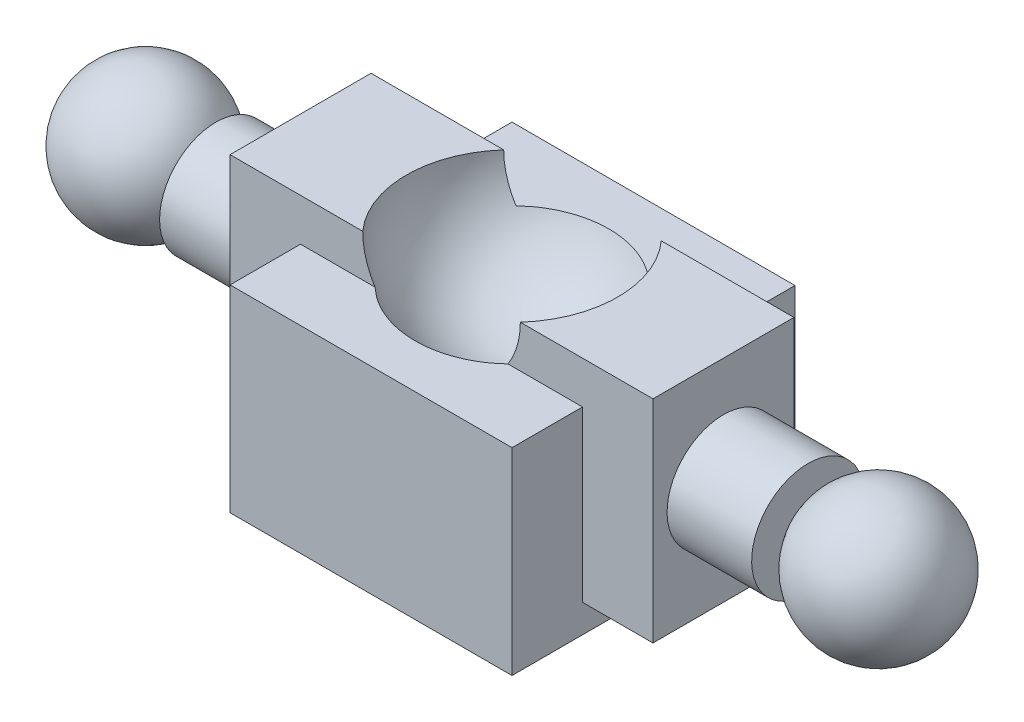
SolidWorks part; units mm, degrees
ref_plane "Front Plane" through (0, 0, 0) normal (0, 0, 1) x (1, 0, 0)
ref_plane "Top Plane" through (0, 0, 0) normal (0, 1, 0) x (1, 0, 0)
ref_plane "Right Plane" through (0, 0, 0) normal (1, 0, 0) x (0, 0, -1)
sketch "Sketch1" plane through (0, 0, 0) normal (0, 0, 1) x (1, 0, 0)
  line L1 (-11.2928, 4.8194) -> (18.7072, 4.8194)
  line L2 (-11.2928, 4.8194) -> (-11.2928, -10.1806)
  line L3 (-11.2928, -10.1806) -> (18.7072, -10.1806)
  line L4 (18.7072, 4.8194) -> (18.7072, -10.1806)
  dimension "D1" = 30
  dimension "D2" = 15
extrude "Boss-Extrude1" add sketch "Sketch1" along normal blind 10 contours L2 L1 L4 L3
sketch "Sketch2" plane through (0, 0, 10) normal (0, 0, 1) x (1, 0, 0)
  line L0 (-11.2928, 4.8194) -> (-11.2928, -10.1806) construction
  line L1 (-6.2928, 1.8194) -> (13.7072, 1.8194)
  line L2 (-6.2928, 1.8194) -> (-6.2928, -12.1806)
  line L3 (-6.2928, -12.1806) -> (13.7072, -12.1806)
  line L4 (13.7072, 1.8194) -> (13.7072, -12.1806)
  line L5 (18.7072, 4.8194) -> (18.7072, -10.1806) construction
  line L6 (-11.2928, 4.8194) -> (18.7072, 4.8194) construction
  line L7 (-11.2928, -10.1806) -> (18.7072, -10.1806) construction
  line L8 (-6.2928, -12.1806) -> (13.7072, -12.1806)
  line L9 (-6.2928, -12.1806) -> (-6.2928, -11.6554)
  line L11 (13.7072, -12.1806) -> (13.7072, -11.6554)
  dimension "D1" = 5
  dimension "D2" = 5
  dimension "D3" = 3
  dimension "D4" = 2
extrude "Boss-Extrude2" add sketch "Sketch2" along normal blind 5 contours L2 L1 L4 L3
sketch "Sketch3" plane through (0, 0, 0) normal (0, 0, -1) x (-1, 0, 0)
  line L0 (11.2928, 4.8194) -> (-18.7072, 4.8194) construction
  line L1 (6.2928, -12.1806) -> (-13.782, -12.1806)
  line L2 (6.2928, -12.1806) -> (6.2928, 1.8194)
  line L3 (6.2928, 1.8194) -> (-13.782, 1.8194)
  line L4 (-13.782, -12.1806) -> (-13.782, 1.8194)
  dimension "D1" = 3
extrude "Boss-Extrude3" add sketch "Sketch3" along normal blind 5 contours L2 L1 L4 L3
sketch "Sketch4" plane through (0, -10.1806, 0) normal (0, -1, 0) x (1, 0, 0)
  line L1 (-6.2928, 10) -> (13.7072, 10)
  line L2 (-6.2928, 10) -> (-6.2928, 0)
  line L3 (-6.2928, 0) -> (13.7072, 0)
  line L4 (13.7072, 10) -> (13.7072, 0)
extrude "Boss-Extrude4" add sketch "Sketch4" along normal blind 2
sketch "Sketch5" plane through (18.7072, 0, 0) normal (1, 0, 0) x (0, 0, -1)
  circle A0 centre (-5, -2.6514) radius 4
  dimension "D1" = 8
extrude "Boss-Extrude6" add sketch "Sketch5" along normal blind 6 contours A0
sketch "Sketch6" plane through (-11.2928, 0, 0) normal (-1, 0, 0) x (0, 0, 1)
  circle A0 centre (5, -2.6806) radius 4
  dimension "D1" = 8
extrude "Boss-Extrude7" add sketch "Sketch6" along normal blind 6
sketch "Sketch7" plane through (0, 4.8194, 0) normal (0, 1, 0) x (1, 0, 0)
  line L0 (3.7072, 2.5) -> (3.7072, -12.5)
  arc A0 (3.7072, 2.5) -> (3.7072, -12.5) centre (3.7072, -5) ccw
  dimension "D1" = 15
sketch "Sketch8" plane through (-17.2928, 0, 0) normal (-1, 0, 0) x (0, 0, 1)
  circle A0 centre (5, -2.6806) radius 1.5
  dimension "D1" = 3
extrude "Boss-Extrude9" add sketch "Sketch8" along normal blind 5
sketch "Sketch9" plane through (-22.2928, 0, 0) normal (-1, 0, 0) x (0, 0, 1)
  line L1 (5, 2.3486) -> (5, -7.6514)
  arc A5 (5, 2.3486) -> (5, -7.6514) centre (5, -2.6514) ccw
sketch "Sketch10" plane through (24.7072, 0, 0) normal (1, 0, 0) x (0, 0, -1)
  circle A0 centre (-5, -2.6514) radius 1.5
extrude "Boss-Extrude10" add sketch "Sketch10" along normal blind 5 contours A0
sketch "Sketch11" plane through (29.7072, 0, 0) normal (1, 0, 0) x (0, 0, -1)
  line L1 (-5, 2.3486) -> (-5, -7.6514)
  arc A4 (-5, 2.3486) -> (-5, -7.6514) centre (-5, -2.6514) ccw
revolve "Revolve3" add sketch "Sketch9" angle 360 about L1
revolve "Revolve4" add sketch "Sketch11" angle 360 about L1
revolve "Cut-Revolve2" cut sketch "Sketch7" angle 360 about L0
